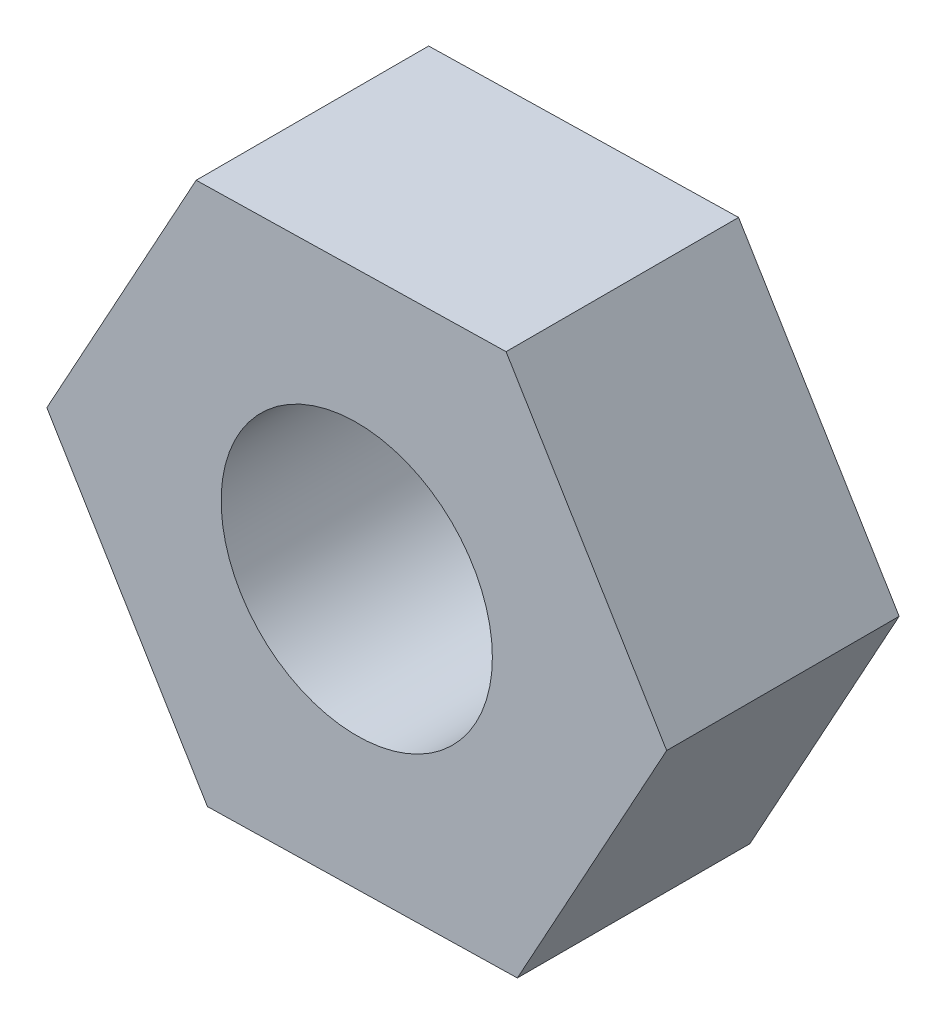
SolidWorks part; units mm, degrees
ref_plane "Front Plane" through (0, 0, 0) normal (0, 0, 1) x (1, 0, 0)
ref_plane "Top Plane" through (0, 0, 0) normal (0, 1, 0) x (1, 0, 0)
ref_plane "Right Plane" through (0, 0, 0) normal (1, 0, 0) x (0, 0, -1)
sketch "Sketch1" plane through (0, 0, 0) normal (0, 0, 1) x (1, 0, 0)
  line L1 (1.9269, 3.5053) -> (-2.0722, 3.4214)
  line L2 (-2.0722, 3.4214) -> (-3.9991, -0.0839)
  line L3 (-3.9991, -0.0839) -> (-1.9269, -3.5053)
  line L4 (-1.9269, -3.5053) -> (2.0722, -3.4214)
  line L5 (2.0722, -3.4214) -> (3.9991, 0.0839)
  line L6 (3.9991, 0.0839) -> (1.9269, 3.5053)
  circle A0 centre (0, 0) radius 3.4641 construction
  circle A1 centre (0, 0) radius 1.75
  dimension "D2" = 3.5
  dimension "D1" = 4
extrude "Boss-Extrude1" add sketch "Sketch1" along normal blind 3
